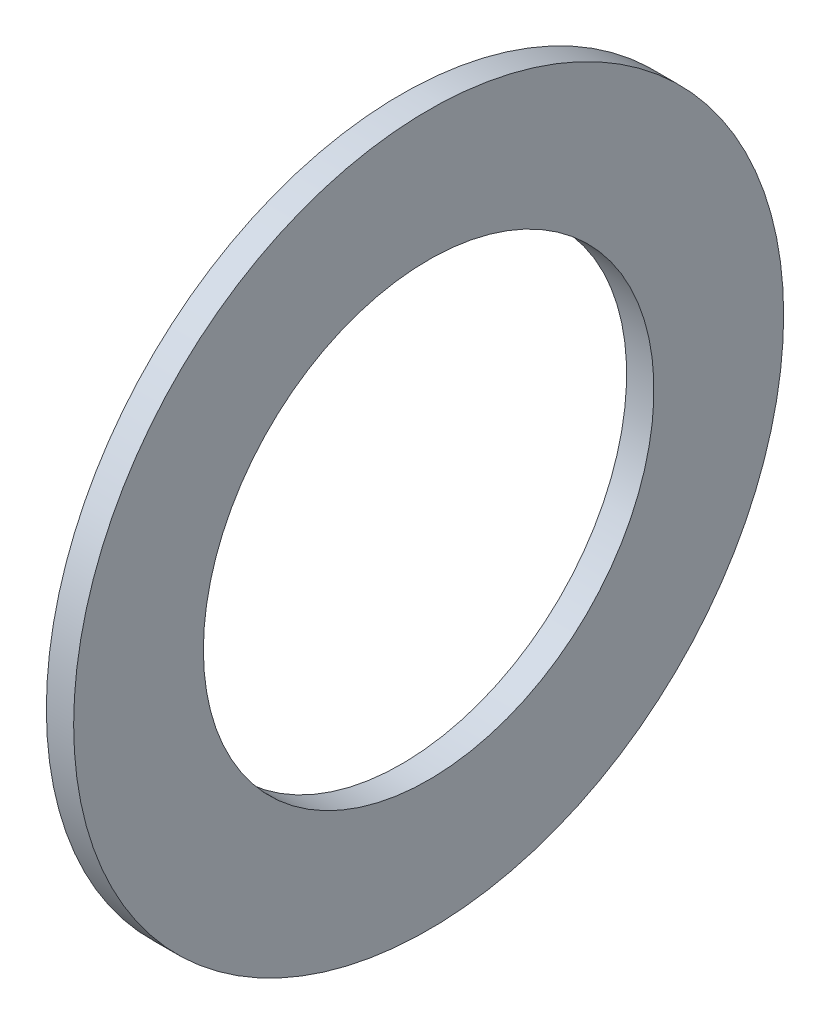
SolidWorks part; units mm, degrees
material "1.0406 (C25)"
ref_plane "Plane1" through (0, 0, 0) normal (0, 0, 1) x (1, 0, 0)
ref_plane "Plane2" through (0, 0, 0) normal (0, 1, 0) x (1, 0, 0)
ref_plane "Plane3" through (0, 0, 0) normal (1, 0, 0) x (0, 0, -1)
sketch "Sketch1" plane through (0, 0, 0) normal (0, 0, 1) x (1, 0, 0)
  line L0 (-34.925, 0) -> (9.525, 0) construction
  line L1 (0, 8.25) -> (0, 13)
  line L2 (0, 13) -> (-1, 13)
  line L3 (-1, 13) -> (-1, 8.25)
  line L4 (-1, 8.25) -> (0, 8.25)
  dimension "Thickness" = 1
  dimension "Inside_dia" = 16.5
  dimension "Outside_dia" = 26
revolve "Base-Revolve" add sketch "Sketch1" angle 360 about L0
